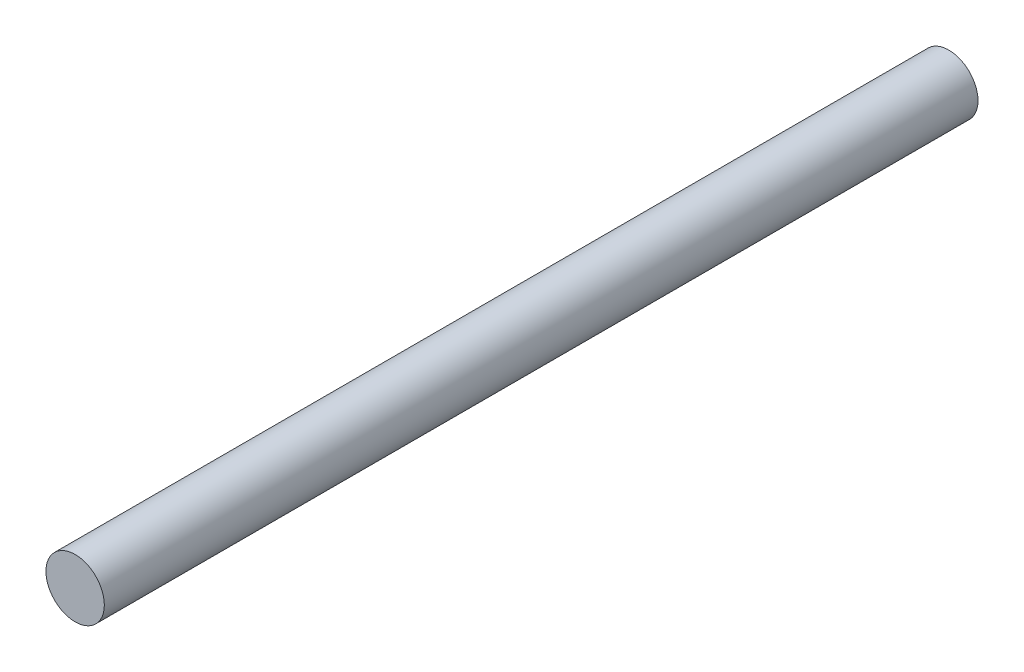
SolidWorks part; units mm, degrees
ref_plane "Front Plane" through (0, 0, 0) normal (0, 0, 1) x (1, 0, 0)
ref_plane "Top Plane" through (0, 0, 0) normal (0, 1, 0) x (1, 0, 0)
ref_plane "Right Plane" through (0, 0, 0) normal (1, 0, 0) x (0, 0, -1)
sketch "Sketch1" plane through (0, 0, 0) normal (0, 0, 1) x (1, 0, 0)
  circle A0 centre (0, 0) radius 6.35
  dimension "D1" = 12.7
extrude "Boss-Extrude1" add sketch "Sketch1" against normal blind 190
